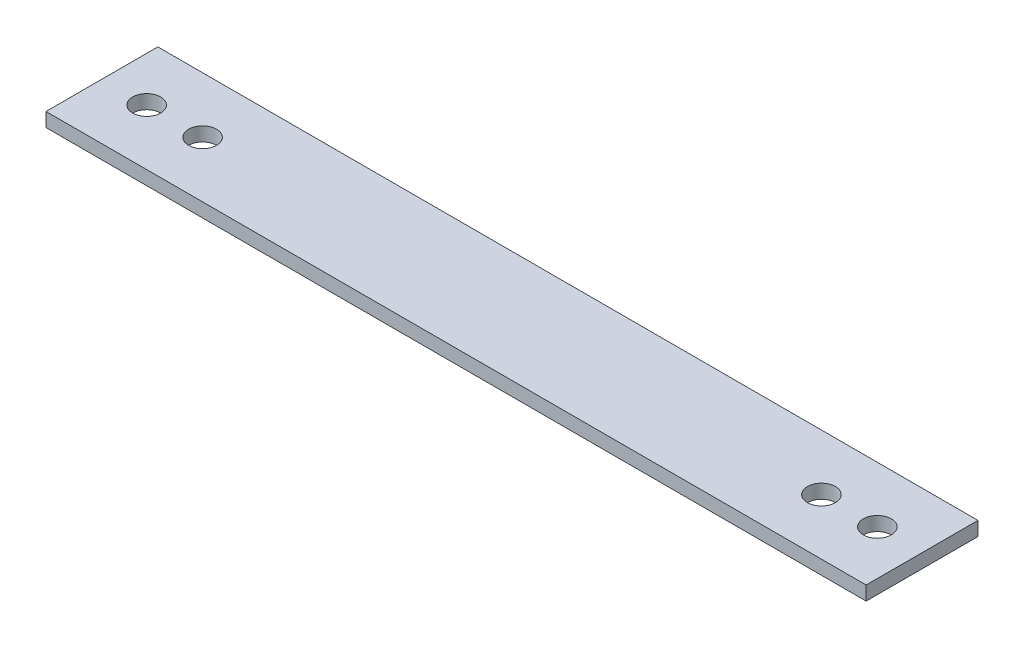
SolidWorks part; units mm, degrees
ref_plane "Front Plane" through (0, 0, 0) normal (0, 0, 1) x (1, 0, 0)
ref_plane "Top Plane" through (0, 0, 0) normal (0, 1, 0) x (1, 0, 0)
ref_plane "Right Plane" through (0, 0, 0) normal (1, 0, 0) x (0, 0, -1)
sketch "Sketch2" plane through (0, 0, 0) normal (0, 1, 0) x (1, 0, 0)
  line L1 (-139.7, -19.05) -> (139.7, -19.05)
  line L2 (-139.7, -19.05) -> (-139.7, 19.05)
  line L3 (-139.7, 19.05) -> (139.7, 19.05)
  line L4 (139.7, -19.05) -> (139.7, 19.05)
  line L5 (0, 19.05) -> (0, -19.05) construction
  line L6 (-139.7, 0) -> (139.7, 0) construction
  circle A0 centre (-124.46, 0) radius 4.7625
  circle A1 centre (-105.41, 0) radius 4.7625
  circle A2 centre (124.46, 0) radius 4.7625
  circle A3 centre (105.41, 0) radius 4.7625
  point P0 (0, 0)
  dimension "D3" = 9.525
  dimension "D1" = 38.1
  dimension "D2" = 279.4
  dimension "D4" = 19.05
  dimension "D5" = 15.24
extrude "Boss-Extrude1" add sketch "Sketch2" along normal blind 4.7625
